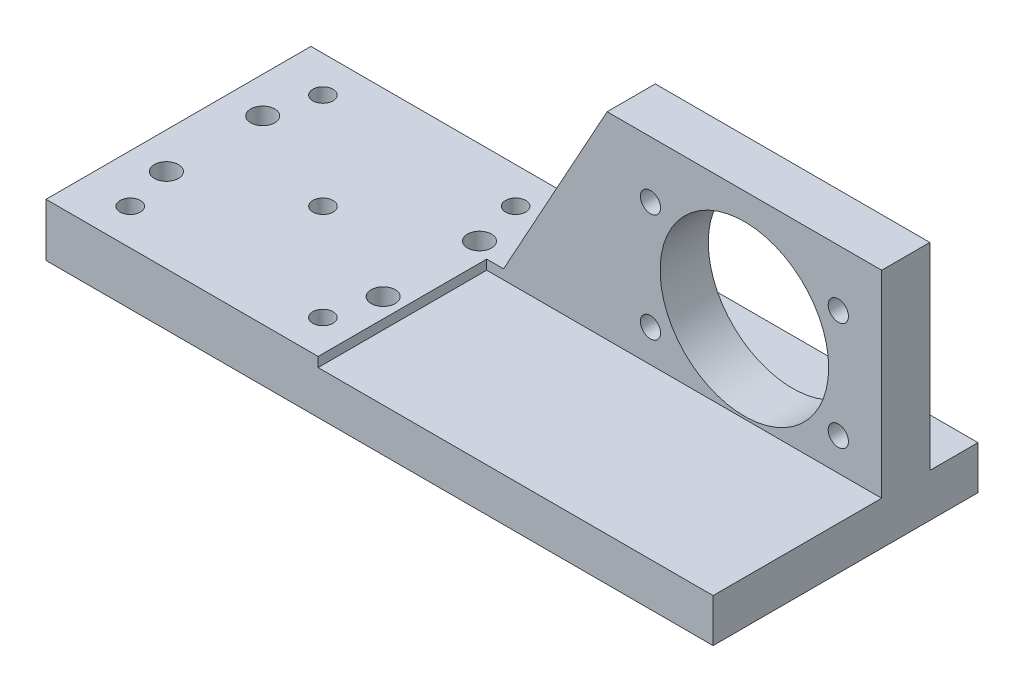
SolidWorks part; units mm, degrees
ref_plane "정면" through (0, 0, 0) normal (0, 0, 1) x (1, 0, 0)
ref_plane "윗면" through (0, 0, 0) normal (0, 1, 0) x (1, 0, 0)
ref_plane "우측면" through (0, 0, 0) normal (1, 0, 0) x (0, 0, -1)
sketch "스케치1" plane through (0, 0, 0) normal (0, 1, 0) x (1, 0, 0)
  line L1 (0, 0) -> (138.5, 0)
  line L2 (0, 0) -> (0, 55)
  line L3 (0, 55) -> (138.5, 55)
  line L4 (138.5, 0) -> (138.5, 55)
  dimension "D1" = 138.5
  dimension "D2" = 55
extrude "보스-돌출1" add sketch "스케치1" along normal blind 11
ref_plane "평면1" through (0, 0, -45) normal (0, 0, -1) x (-1, 0, 0)
sketch "스케치2" plane through (0, 0, -45) normal (0, 0, -1) x (-1, 0, 0)
  line L0 (-138.5, 11) -> (-138.5, 50)
  line L1 (-138.5, 50) -> (-81.5, 50)
  line L2 (-81.5, 50) -> (-60, 11)
  line L3 (0, 11) -> (-138.5, 11) construction
  line L4 (-138.5, 11) -> (-60, 11)
  line L5 (0, 0) -> (-138.5, 0) construction
  dimension "D1" = 21.5
  dimension "D2" = 57
  dimension "D3" = 50
extrude "보스-돌출2" add sketch "스케치2" against normal blind 10
sketch "스케치3" plane through (0, 11, 0) normal (0, 1, 0) x (1, 0, 0)
  line L1 (138.5, 55) -> (56.5, 55)
  line L2 (138.5, 55) -> (138.5, 45)
  line L3 (138.5, 45) -> (56.5, 45)
  line L4 (56.5, 55) -> (56.5, 45)
  dimension "D1" = 10
  dimension "D2" = 82
extrude "컷-돌출1" cut sketch "스케치3" against normal blind 2
sketch "스케치4" plane through (0, 11, 0) normal (0, 1, 0) x (1, 0, 0)
  line L0 (0, 0) -> (138.5, 0) construction
  line L1 (138.5, 35) -> (56.5, 35)
  line L2 (138.5, 35) -> (138.5, 0)
  line L3 (138.5, 0) -> (56.5, 0)
  line L4 (56.5, 35) -> (56.5, 0)
  dimension "D1" = 82
extrude "컷-돌출2" cut sketch "스케치4" against normal blind 2
sketch "스케치5" plane through (0, 0, -35) normal (0, 0, 1) x (1, 0, 0)
  line L0 (138.5, 50) -> (138.5, 9) construction
  line L1 (0, 0) -> (138.5, 0) construction
  line L2 (81.5, 50) -> (138.5, 50) construction
  circle A0 centre (110, 27) radius 17.5
  circle A1 centre (129.5, 38.25) radius 2.5
  circle A2 centre (90.5, 38.25) radius 2.5
  circle A3 centre (90.5, 15.75) radius 2.5
  circle A4 centre (129.5, 15.75) radius 2.5
  point P17 (129.5, 38.25)
  point P18 (90.5, 38.25)
  point P19 (129.5, 15.75)
  point P20 (90.5, 15.75)
  dimension "D3" = 35
  dimension "D8" = 5
  dimension "D1" = 28.5
  dimension "D2" = 27
  dimension "D4" = 9
  dimension "D5" = 39
  dimension "D6" = 11.75
  dimension "D7" = 22.5
extrude "컷-돌출3" cut sketch "스케치5" against normal through all contours A0
sketch "스케치8" plane through (0, 0, -35) normal (0, 0, 1) x (1, 0, 0)
  point P0 (90.5, 38.25)
  point P3 (129.5, 38.25)
  point P6 (129.5, 15.75)
  point P9 (90.5, 15.75)
hole_wizard "M5 나사 구멍1" positions "스케치8" profile "스케치7" tap size "M5" standard "ISO" end condition through all
sketch "스케치7" plane through (90.5, 38.25, -35) normal (1, 0, 0) x (0, -1, 0)
  line L0 (0, 0) -> (0, 20)
  line L1 (0, 20) -> (2.1, 20)
  line L2 (2.1, 20) -> (2.1, 0)
  line L5 (2.1, 0) -> (0, 0)
  line L11 (0, -6.35) -> (0, 107.95) construction
  dimension "관통 탭 드릴 지름" = 4.2
  dimension "관통 탭 드릴 깊이" = 20
cosmetic thread "구멍 나사산1" parameters "D2"=5
cosmetic thread "구멍 나사산2" parameters "D2"=5
cosmetic thread "구멍 나사산3" parameters "D2"=5
cosmetic thread "구멍 나사산4" parameters "D2"=5
sketch "스케치9" plane through (0, 0, 0) normal (0, 1, 0) x (1, 0, 0)
  line L0 (0, 0) -> (56.5, 0) construction
  line L1 (0, 55) -> (0, 0) construction
  circle A0 centre (7.5, 37.5) radius 4
  circle A1 centre (52.5, 37.5) radius 4
  circle A2 centre (7.5, 17.5) radius 4
  circle A3 centre (52.5, 17.5) radius 4
  point P8 (0, 0)
  point P9 (0, 0)
  point P10 (0, 0)
  point P11 (0, 0)
  dimension "D1" = 8
  dimension "D2" = 17.5
  dimension "D3" = 20
  dimension "D4" = 7.5
  dimension "D5" = 45
extrude "컷-돌출5" cut sketch "스케치9" along normal blind 5
sketch "스케치10" plane through (0, 5, 0) normal (0, -1, 0) x (1, 0, 0)
  circle A0 centre (52.5, -17.5) radius 2.5
  circle A1 centre (52.5, -37.5) radius 2.5
  circle A2 centre (7.5, -37.5) radius 2.5
  circle A3 centre (7.5, -17.5) radius 2.5
  dimension "D1" = 5
extrude "컷-돌출6" cut sketch "스케치10" against normal through all
sketch "스케치11" plane through (0, 11, 0) normal (0, 1, 0) x (1, 0, 0)
  line L0 (0, 0) -> (56.5, 0) construction
  line L1 (0, 55) -> (0, 0) construction
  point P0 (10, 47.5)
  point P1 (50, 47.5)
  point P2 (10, 7.5)
  point P3 (50, 7.5)
  point P6 (30, 27.5)
  dimension "D1" = 7.5
  dimension "D2" = 40
  dimension "D3" = 20
  dimension "D4" = 20
  dimension "D5" = 10
  dimension "D6" = 20
hole_wizard "M5 나사 구멍2" positions "스케치11" profile "스케치12" tap size "M5" standard "ISO" end condition through all
sketch "스케치12" plane through (10, 11, -47.5) normal (1, 0, 0) x (0, 0, 1)
  line L0 (0, 0) -> (0, 11)
  line L1 (0, 11) -> (2.1, 11)
  line L2 (2.1, 11) -> (2.1, 0)
  line L5 (2.1, 0) -> (0, 0)
  line L11 (0, -6.35) -> (0, 107.95) construction
  dimension "관통 탭 드릴 지름" = 4.2
  dimension "관통 탭 드릴 깊이" = 11
cosmetic thread "구멍 나사산5" parameters "D2"=5
cosmetic thread "구멍 나사산6" parameters "D2"=5
cosmetic thread "구멍 나사산7" parameters "D2"=5
cosmetic thread "구멍 나사산8" parameters "D2"=5
cosmetic thread "구멍 나사산9" parameters "D2"=5
